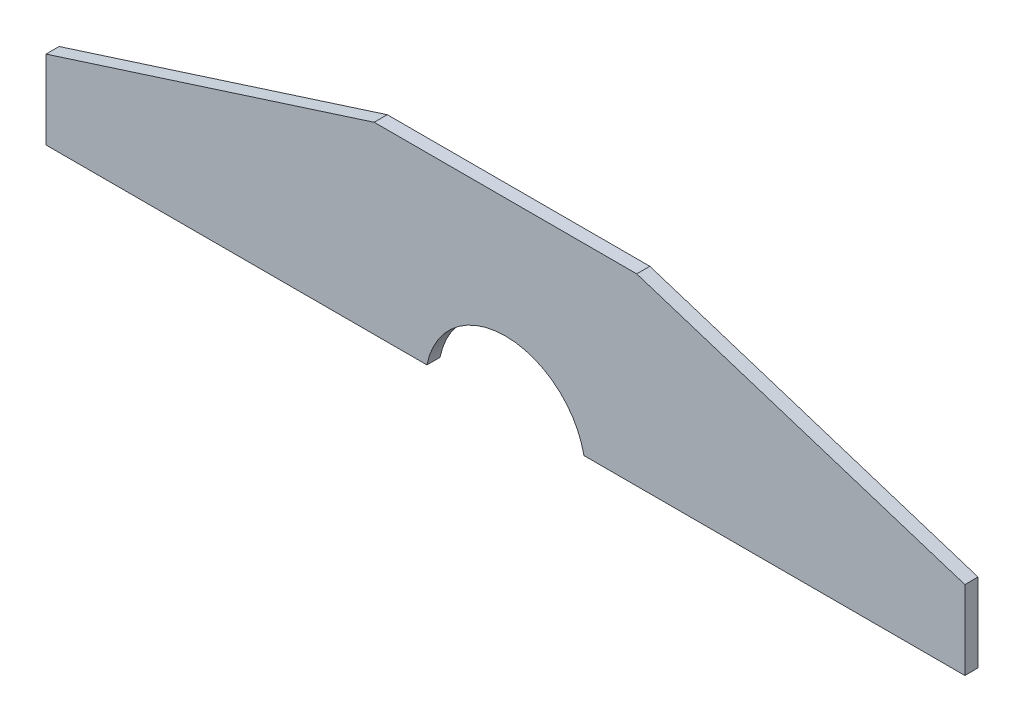
SolidWorks part; units mm, degrees
material "CK45"
ref_plane "Front Plane" through (0, 0, 0) normal (0, 0, 1) x (1, 0, 0)
ref_plane "Top Plane" through (0, 0, 0) normal (0, 1, 0) x (1, 0, 0)
ref_plane "Right Plane" through (0, 0, 0) normal (1, 0, 0) x (0, 0, -1)
sketch "Sketch1" plane through (0, 0, 0) normal (0, 0, 1) x (1, 0, 0)
  line L0 (-175, 36) -> (-50, 76)
  line L1 (-175, 6) -> (-29.904, 6)
  line L2 (-175, 6) -> (-175, 36)
  line L3 (-50, 76) -> (50, 76)
  line L4 (175, 6) -> (175, 36)
  line L5 (50, 76) -> (175, 36)
  line L6 (29.904, 6) -> (175, 6)
  arc A0 (29.904, 6) -> (-29.904, 6) centre (0, 0) ccw
  point P5 (0, 76)
  dimension "D1" = 61
  dimension "D2" = 350
  dimension "D3" = 100
  dimension "D4" = 30
  dimension "D5" = 70
  dimension "D6" = 6
extrude "Boss-Extrude1" add sketch "Sketch1" along normal blind 5
